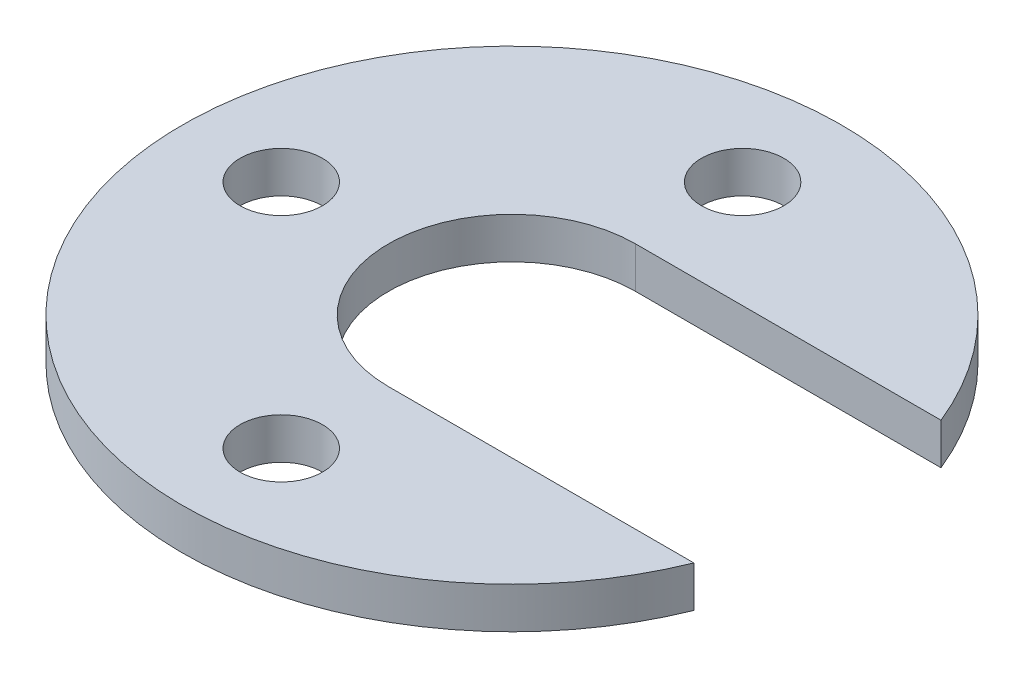
SolidWorks part; units mm, degrees
ref_plane "Front Plane" through (0, 0, 0) normal (0, 0, 1) x (1, 0, 0)
ref_plane "Top Plane" through (0, 0, 0) normal (0, 1, 0) x (1, 0, 0)
ref_plane "Right Plane" through (0, 0, 0) normal (1, 0, 0) x (0, 0, -1)
sketch "Sketch1" plane through (0, 0, 0) normal (0, 1, 0) x (1, 0, 0)
  line L0 (0, 15) -> (37.081, 15)
  line L1 (0, -15) -> (37.081, -15)
  arc A0 (37.081, 15) -> (37.081, -15) centre (0, 0) ccw
  circle A1 centre (-28, 0) radius 5
  circle A2 centre (0, 28) radius 5
  circle A4 centre (0, -28) radius 5
  circle A5 centre (28, 0) radius 5 [skipped]
  arc A6 (0, 15) -> (0, -15) centre (0, 0) ccw
  point P14 (0, 0)
  dimension "D1" = 80
  dimension "D2" = 10
  dimension "D5" = 30
  dimension "D3" = 28
  dimension "D4" = 4
extrude "Boss-Extrude1" add sketch "Sketch1" along normal blind 5
